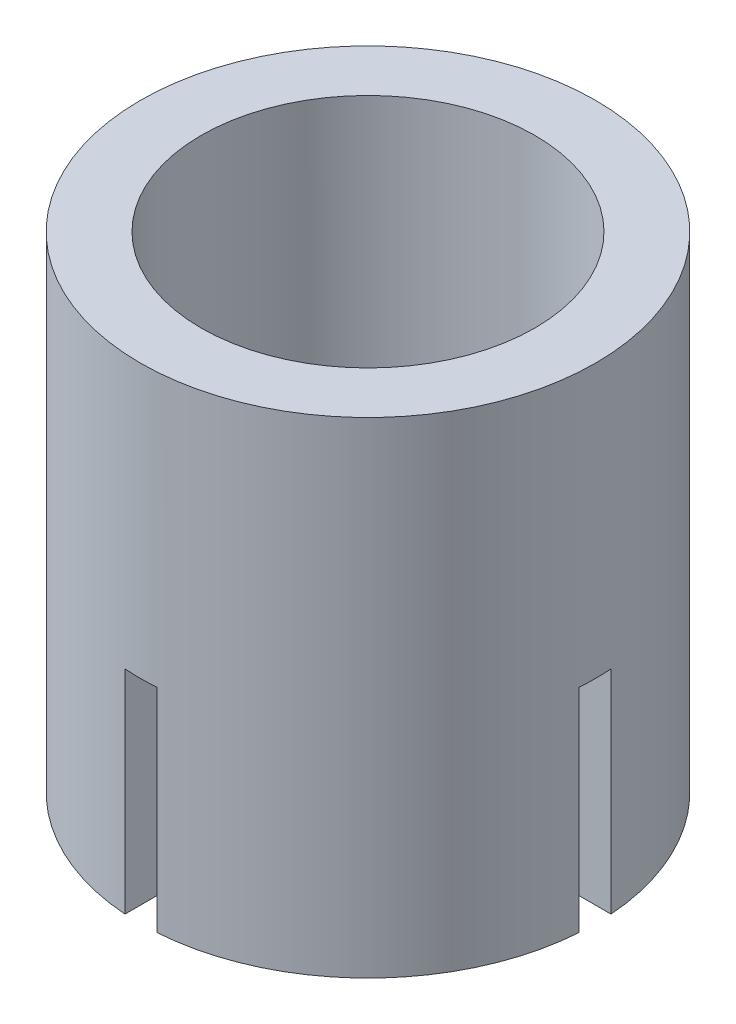
SolidWorks part; units mm, degrees
ref_plane "Front Plane" through (0, 0, 0) normal (0, 0, 1) x (1, 0, 0)
ref_plane "Top Plane" through (0, 0, 0) normal (0, 1, 0) x (1, 0, 0)
ref_plane "Right Plane" through (0, 0, 0) normal (1, 0, 0) x (0, 0, -1)
sketch "Sketch1" plane through (0, 0, 0) normal (0, 1, 0) x (1, 0, 0)
  circle A0 centre (0, 0) radius 3
  circle A1 centre (0, 0) radius 7.5
  dimension "D1" = 6
  dimension "D2" = 15
extrude "Boss-Extrude1" add sketch "Sketch1" along normal blind 6
sketch "Sketch2" plane through (0, 6, 0) normal (0, 1, 0) x (1, 0, 0)
  circle A0 centre (0, 0) radius 7.5
  circle A1 centre (0, 0) radius 5.5
  circle A2 centre (0, 0) radius 7.5 construction
  dimension "D1" = 11
extrude "Boss-Extrude2" add sketch "Sketch2" along normal blind 10
sketch "Sketch3" plane through (0, 0, 0) normal (0, -1, 0) x (1, 0, 0)
  line L1 (-10.4593, 0.5274) -> (10.4593, 0.5274)
  line L2 (-10.4593, 0.5274) -> (-10.4593, -0.5274)
  line L3 (-10.4593, -0.5274) -> (10.4593, -0.5274)
  line L4 (10.4593, 0.5274) -> (10.4593, -0.5274)
  line L5 (-10.4593, 0.5274) -> (10.4593, -0.5274) construction
  line L6 (-10.4593, -0.5274) -> (10.4593, 0.5274) construction
  line L7 (-0.5274, 10.5326) -> (0.5274, 10.5326)
  line L8 (-0.5274, 10.5326) -> (-0.5274, -10.5326)
  line L9 (-0.5274, -10.5326) -> (0.5274, -10.5326)
  line L10 (0.5274, 10.5326) -> (0.5274, -10.5326)
  line L11 (-0.5274, 10.5326) -> (0.5274, -10.5326) construction
  line L12 (-0.5274, -10.5326) -> (0.5274, 10.5326) construction
  point P0 (0, 0)
  point P6 (0, 0)
  circle M6 centre (0, 0) radius 7.5
  circle M7 centre (0, 0) radius 3
extrude "Cut-Extrude1" cut sketch "Sketch3" against normal blind 7 contours L10 L7 L8 M6 | L2 L3 L1 M6 | L10 L8 M6 M7 | L3 L1 M7 M6 | L10 L8 M7 M6 | L3 L1 M6 M7
